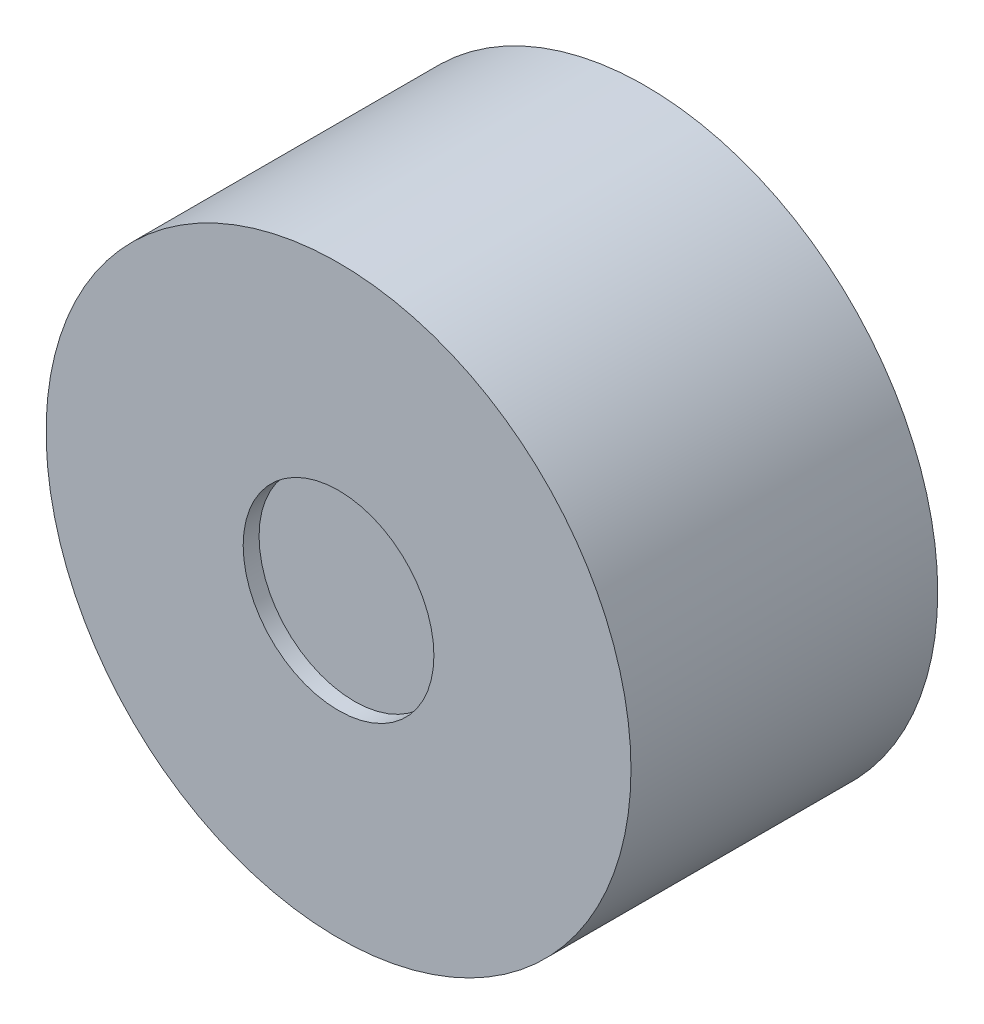
SolidWorks part; units mm, degrees
ref_plane "Alzado" through (0, 0, 0) normal (0, 0, 1) x (1, 0, 0)
ref_plane "Planta" through (0, 0, 0) normal (0, 1, 0) x (1, 0, 0)
ref_plane "Vista lateral" through (0, 0, 0) normal (1, 0, 0) x (0, 0, -1)
sketch "Croquis1" plane through (0, 0, 0) normal (0, 0, 1) x (1, 0, 0)
  circle A0 centre (0, 0) radius 18.4
  dimension "D1" = 36.8
extrude "Saliente-Extruir1" add sketch "Croquis1" along normal blind 24.3
sketch "Croquis2" plane through (0, 0, 24.3) normal (0, 0, 1) x (1, 0, 0)
  circle A0 centre (0, 0) radius 3
  circle A1 centre (0, 0) radius 9.5 construction
  circle A2 centre (0, 9.5) radius 1.25
  circle A3 centre (9.5, 0) radius 1.25
  circle A4 centre (0, -9.5) radius 1.25
  circle A5 centre (-9.5, 0) radius 1.25
  point P15 (0, 0)
  dimension "D1" = 6
  dimension "D2" = 19
  dimension "D3" = 2.5
  dimension "D4" = 4
extrude "Cortar-Extruir1" cut sketch "Croquis2" against normal blind 5
sketch "Croquis3" plane through (0, 0, 0) normal (0, 0, -1) x (-1, 0, 0)
  circle A0 centre (0, 0) radius 10 construction
  circle A1 centre (-10, 0) radius 1.25
  circle A2 centre (0, 10) radius 1.25
  circle A3 centre (10, 0) radius 1.25
  circle A4 centre (0, -10) radius 1.25
  point P14 (0, 0)
  dimension "D1" = 20
  dimension "D2" = 2.5
  dimension "D3" = 4
extrude "Cortar-Extruir2" cut sketch "Croquis3" against normal blind 5
sketch "Croquis6" plane through (0, 0, 24.3) normal (0, 0, 1) x (1, 0, 0)
  circle A0 centre (0, 0) radius 18.4
extrude "Cortar-Extruir3" cut sketch "Croquis6" against normal blind 5
sketch "Croquis7" plane through (0, 0, 19.3) normal (0, 0, 1) x (1, 0, 0)
  circle A0 centre (0, 0) radius 6
extrude "Cortar-Extruir4" cut sketch "Croquis7" against normal blind 1
